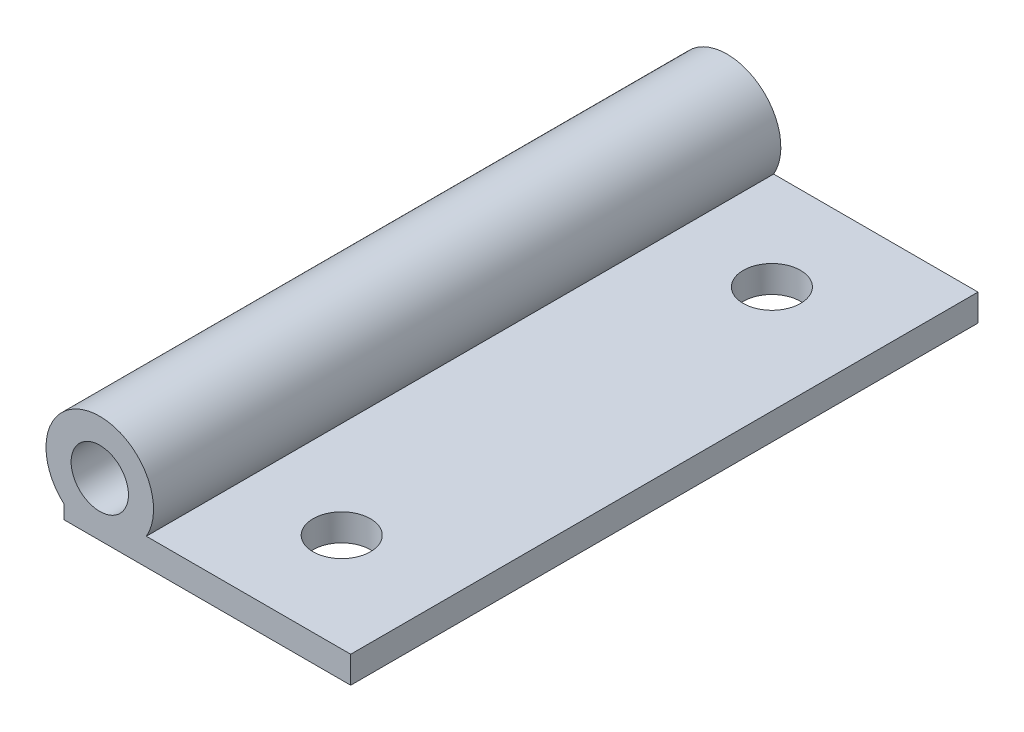
SolidWorks part; units mm, degrees
ref_plane "前视基准面" through (0, 0, 0) normal (0, 0, 1) x (1, 0, 0)
ref_plane "上视基准面" through (0, 0, 0) normal (0, 1, 0) x (1, 0, 0)
ref_plane "右视基准面" through (0, 0, 0) normal (1, 0, 0) x (0, 0, -1)
other "Configuration Table"
sketch "草图1" plane through (0, 0, 0) normal (0, 0, 1) x (1, 0, 0)
  circle A0 centre (0, 0) radius 3
extrude "中间活动轴套" add sketch "草图1" along normal blind 35 from offset 17.5
sketch "草图2" plane through (0, 0, 0) normal (0, 0, 1) x (1, 0, 0)
  line L0 (-2, -3) -> (14, -3)
  line L1 (14, -3) -> (14, -1.5)
  line L2 (14, -1.5) -> (-2, -1.5)
  line L3 (-2, -1.5) -> (-2, -3)
extrude "摄像头板固定叶" add sketch "草图2" along normal blind 35 from offset 17.5
sketch "草图3" plane through (0, 0, 0) normal (0, 0, 1) x (1, 0, 0)
  circle A0 centre (0, 0) radius 1.6
extrude "D3p2活动转轴孔" cut sketch "草图3" along normal blind 40 from offset 20
sketch "草图4" plane through (0, 0, 0) normal (0, 1, 0) x (1, 0, 0)
  circle A0 centre (8, 12) radius 1.6
extrude "吊板M3安装孔" cut sketch "草图4" along normal blind 100 and the other way blind 100
sketch "草图5" plane through (0, 0, 0) normal (0, 1, 0) x (1, 0, 0)
  circle A0 centre (8, -12) radius 1.6
extrude "切除-拉伸3" cut sketch "草图5" along normal blind 100 and the other way blind 100
